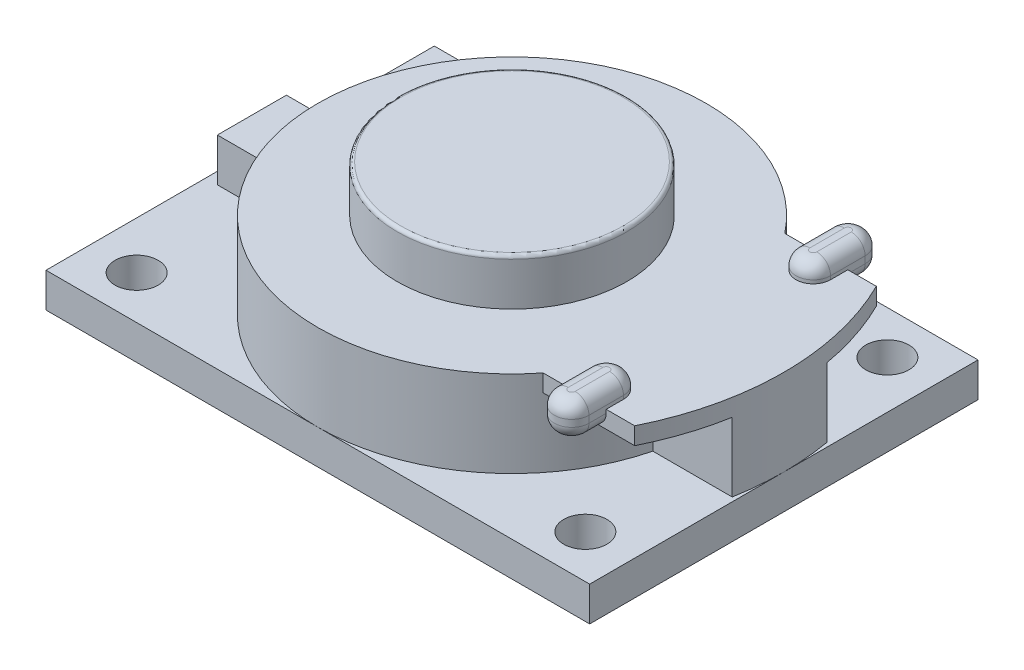
SolidWorks part; units mm, degrees
ref_plane "Front Plane" through (0, 0, 0) normal (0, 0, 1) x (1, 0, 0)
ref_plane "Top Plane" through (0, 0, 0) normal (0, 1, 0) x (1, 0, 0)
ref_plane "Right Plane" through (0, 0, 0) normal (1, 0, 0) x (0, 0, -1)
sketch "Sketch1" plane through (0, 0, 0) normal (0, 1, 0) x (1, 0, 0)
  line L1 (-20.0025, 14.2875) -> (20.0025, 14.2875)
  line L2 (-20.0025, 14.2875) -> (-20.0025, -14.2875)
  line L3 (-20.0025, -14.2875) -> (20.0025, -14.2875)
  line L4 (20.0025, 14.2875) -> (20.0025, -14.2875)
  line L5 (-20.0025, 14.2875) -> (20.0025, -14.2875) construction
  line L6 (-20.0025, -14.2875) -> (20.0025, 14.2875) construction
  point P0 (0, 0)
  dimension "D1" = 40.005
  dimension "D2" = 28.575
extrude "Boss-Extrude1" add sketch "Sketch1" along normal blind 2.54
sketch "Sketch2" plane through (0, 0, 0) normal (0, 1, 0) x (1, 0, 0)
  line L1 (-16.51, -11.1125) -> (16.51, -11.1125) construction
  line L2 (-16.51, -11.1125) -> (-16.51, 11.1125) construction
  line L3 (-16.51, 11.1125) -> (16.51, 11.1125) construction
  line L4 (16.51, -11.1125) -> (16.51, 11.1125) construction
  line L5 (-16.51, -11.1125) -> (16.51, 11.1125) construction
  line L6 (-16.51, 11.1125) -> (16.51, -11.1125) construction
  circle A0 centre (-16.51, 11.1125) radius 1.5875
  circle A1 centre (16.51, 11.1125) radius 1.5875
  circle A2 centre (16.51, -11.1125) radius 1.5875
  circle A3 centre (-16.51, -11.1125) radius 1.5875
  point P0 (0, 0)
  dimension "D3" = 3.175
  dimension "D1" = 33.02
  dimension "D2" = 22.225
extrude "Cut-Extrude1" cut sketch "Sketch2" along normal through all
sketch "Sketch3" plane through (0, 2.54, 0) normal (0, 1, 0) x (1, 0, 0)
  line L0 (-20.0025, -14.2875) -> (20.0025, -14.2875) construction
  circle A0 centre (0, 0) radius 14.2875
extrude "Boss-Extrude2" add sketch "Sketch3" along normal blind 6.35
sketch "Sketch4" plane through (0, 8.89, 0) normal (0, 1, 0) x (1, 0, 0)
  circle A0 centre (0, 0) radius 8.4455
  dimension "D1" = 16.891
extrude "Boss-Extrude3" add sketch "Sketch4" along normal blind 3.429
fillet "Fillet1" radius 0.254 1 edges at (0, 12.319, 8.4455)
sketch "Sketch5" plane through (0, 2.54, 0) normal (0, 1, 0) x (1, 0, 0)
  line L1 (-19.1399, 2.54) -> (-13.1368, 2.54)
  line L2 (-19.1399, 2.54) -> (-19.1399, -2.54)
  line L3 (-19.1399, -2.54) -> (-13.1368, -2.54)
  line L4 (-13.1368, 2.54) -> (-13.1368, -2.54)
  line L5 (-19.1399, 2.54) -> (-13.1368, -2.54) construction
  line L6 (-19.1399, -2.54) -> (-13.1368, 2.54) construction
  circle A0 centre (0, 0) radius 14.2875 construction
  point P0 (-16.1383, 0)
  point P6 (-14.0599, 2.54)
  dimension "D1" = 5.08
  dimension "D2" = 5.08
extrude "Boss-Extrude4" add sketch "Sketch5" along normal blind 3.175
sketch "Sketch6" plane through (0, 2.54, 0) normal (0, 1, 0) x (1, 0, 0)
  line L0 (-1000, 0) -> (49000, 0) construction
  line L1 (11.1848, -8.89) -> (17.9184, -8.89)
  line L3 (11.1848, 8.89) -> (17.9184, 8.89)
  arc A0 (17.9184, -8.89) -> (17.9184, 8.89) centre (0, 0) ccw
  arc A1 (0, -14.2875) -> (0, 14.2875) centre (0, 0) ccw construction
  arc A2 (11.1848, -8.89) -> (11.1848, 8.89) centre (0, 0) ccw
  circle A3 centre (0, 0) radius 14.2875 construction
  dimension "D1" = 5.715
  dimension "D2" = 8.89
  dimension "D3" = 8.89
extrude "Boss-Extrude5" add sketch "Sketch6" along normal blind 6.35
sketch "Sketch7" plane through (0, 8.89, 0) normal (0, 1, 0) x (1, 0, 0)
  line L0 (14.5516, 7.62) -> (14.5516, 10.16) construction
  line L1 (13.2816, 7.62) -> (13.2816, 10.16)
  line L2 (15.8216, 7.62) -> (15.8216, 10.16)
  line L3 (-1000, 0) -> (49000, 0) construction
  line L4 (17.9184, 8.89) -> (11.1848, 8.89) construction
  line L5 (14.5516, -7.62) -> (14.5516, -10.16) construction
  line L6 (13.2816, -7.62) -> (13.2816, -10.16)
  line L7 (15.8216, -7.62) -> (15.8216, -10.16)
  arc A0 (13.2816, 7.62) -> (15.8216, 7.62) centre (14.5516, 7.62) ccw
  arc A1 (15.8216, 10.16) -> (13.2816, 10.16) centre (14.5516, 10.16) ccw
  arc A2 (13.2816, -7.62) -> (15.8216, -7.62) centre (14.5516, -7.62) cw
  arc A3 (15.8216, -10.16) -> (13.2816, -10.16) centre (14.5516, -10.16) cw
  point P2 (14.5516, 8.89)
  point P15 (14.5516, -8.89)
  dimension "D1" = 2.54
  dimension "D2" = 2.54
extrude "Boss-Extrude6" add sketch "Sketch7" along normal mid plane 2.54
fillet "Fillet2" radius 1.016 14 edges at (15.8216, 7.62, -9.525) (13.2816, 7.62, -9.525) (13.2816, 7.62, 9.525) (15.8216, 7.62, 9.525) (13.2816, 10.16, 8.89) (14.5516, 10.16, 6.35) (15.8216, 10.16, 8.89) (13.2816, 10.16, -8.89) (14.5516, 10.16, -11.43) (15.8216, 10.16, -8.89) (14.5516, 7.62, -11.43) (14.5516, 7.62, 11.43) (14.5516, 10.16, 11.43) (14.5516, 10.16, -6.35)
sketch "Sketch9" plane through (0, 2.54, 0) normal (0, 1, 0) x (1, 0, 0)
  line L0 (0, 14.2875) -> (31.7536, 14.2875)
  line L1 (13.8541, 3.4925) -> (31.7536, 3.4925)
  line L3 (13.8541, -3.4925) -> (31.7536, -3.4925)
  line L4 (31.7536, 3.4925) -> (31.7536, -3.4925) construction
  line L7 (31.7536, 14.2875) -> (31.7536, 3.4925)
  line L8 (0, -14.2875) -> (31.7536, -14.2875)
  line L9 (31.7536, -14.2875) -> (31.7536, -3.4925)
  arc A0 (0, -14.2875) -> (13.8541, -3.4925) centre (0, 0) ccw
  arc A1 (0, -14.2875) -> (11.1848, -8.89) centre (0, 0) ccw construction
  arc A2 (13.8541, 3.4925) -> (0, 14.2875) centre (0, 0) ccw
  point P6 (11.8803, 0)
  point P8 (31.7536, 0)
  dimension "D1" = 6.985
extrude "Cut-Extrude2" cut sketch "Sketch9" along normal blind 5.08
sketch "Sketch8" plane through (0, 2.54, 0) normal (0, 1, 0) x (1, 0, 0)
  circle A0 centre (-16.51, 11.1125) radius 2.3241
  circle A1 centre (16.51, 11.1125) radius 2.3241
  dimension "D1" = 4.6482
